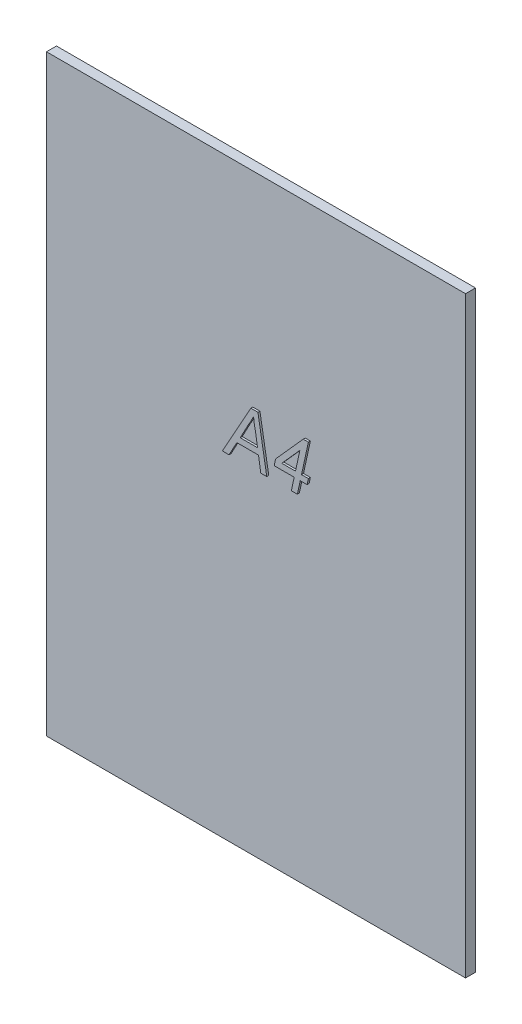
SolidWorks part; units mm, degrees
material "Гофрированная бумага"
ref_plane "Спереди" through (0, 0, 0) normal (0, 0, 1) x (1, 0, 0)
ref_plane "Сверху" through (0, 0, 0) normal (0, 1, 0) x (1, 0, 0)
ref_plane "Справа" through (0, 0, 0) normal (1, 0, 0) x (0, 0, -1)
sketch "Эскиз1" plane through (0, 0, 0) normal (0, 0, 1) x (1, 0, 0)
  line L1 (-105, -148.5) -> (105, -148.5)
  line L2 (-105, -148.5) -> (-105, 148.5)
  line L3 (-105, 148.5) -> (105, 148.5)
  line L4 (105, -148.5) -> (105, 148.5)
  line L5 (0, 148.5) -> (0, -148.5) construction
  line L6 (-105, 0) -> (105, 0) construction
  point P0 (0, 0)
  dimension "D1" = 210
  dimension "D2" = 297
extrude "Бобышка-Вытянуть1" add sketch "Эскиз1" along normal mid plane 5
sketch "Эскиз2" [suppressed] plane through (0, 0, 2.5) normal (0, 0, 1) x (1, 0, 0)
  text T0 "ЕВРОСТАНДАРТ" font "Arial" height in points 22
sketch "Эскиз3" plane through (0, 0, 2.5) normal (0, 0, 1) x (1, 0, 0)
  text T0 "A4" font "Arial" height in points 100
sketch "Эскиз4" [suppressed] plane through (0, 0, 2.5) normal (0, 0, 1) x (1, 0, 0)
  text T0 "A5" font "Arial" height in points 72
extrude "Бобышка-Вытянуть2" [suppressed] add sketch "Эскиз4" along normal blind 1 separate body
extrude "Бобышка-Вытянуть3" [suppressed] add sketch "Эскиз2" along normal blind 1 separate body
extrude "Бобышка-Вытянуть4" add sketch "Эскиз3" along normal blind 1 separate body
